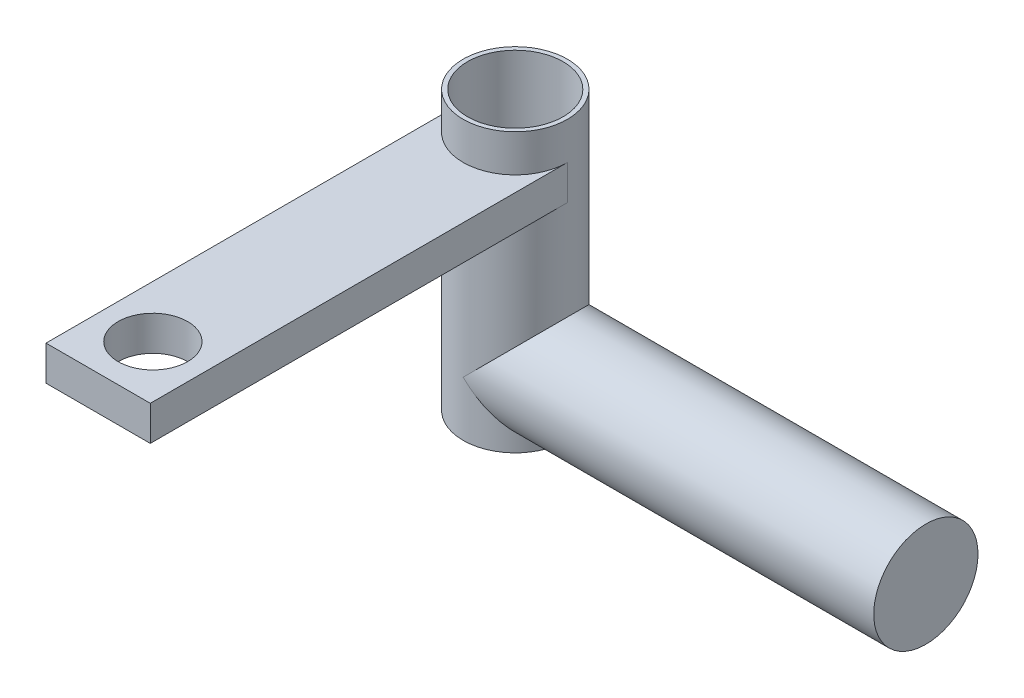
SolidWorks part; units mm, degrees
ref_plane "Front Plane" through (0, 0, 0) normal (0, 0, 1) x (1, 0, 0)
ref_plane "Top Plane" through (0, 0, 0) normal (0, 1, 0) x (1, 0, 0)
ref_plane "Right Plane" through (0, 0, 0) normal (1, 0, 0) x (0, 0, -1)
sketch "Sketch1" plane through (0, 0, 0) normal (0, 1, 0) x (1, 0, 0)
  circle A0 centre (0, 0) radius 9.525
  dimension "D1" = 19.05
extrude "Sleeve" add sketch "Sketch1" along normal blind 50.8
sketch "Sketch2" plane through (0, 0, 0) normal (0, 0, 1) x (1, 0, 0)
  line L0 (0, -10.4775) -> (0, 10.4775) construction
  line L1 (9.525, 43.975) -> (-9.525, 43.975)
  line L2 (9.525, 43.975) -> (9.525, 37.625)
  line L3 (9.525, 37.625) -> (-9.525, 37.625)
  line L4 (-9.525, 43.975) -> (-9.525, 37.625)
  line L5 (9.525, 43.975) -> (-9.525, 37.625) construction
  line L6 (9.525, 37.625) -> (-9.525, 43.975) construction
  point P0 (0, 40.8)
  dimension "D1" = 6.35
  dimension "D2" = 19.05
  dimension "D3" = 40.8
extrude "Bracket" add sketch "Sketch2" along normal blind 76.2
sketch "Sketch4" plane through (0, 0, 0) normal (0, 1, 0) x (1, 0, 0)
  line L0 (0, -27.94) -> (0, 27.94) construction
  circle A0 centre (0, -66.2) radius 6.35
  dimension "D1" = 12.7
  dimension "D2" = 66.2
extrude "Bracket Hole" cut sketch "Sketch4" along normal through all
sketch "Sketch5" plane through (0, 0, 0) normal (1, 0, 0) x (0, 0, -1)
  line L0 (0, 27.94) -> (0, -27.94) construction
  circle A0 centre (0, 10) radius 9.525
  dimension "D2" = 19.05
  dimension "D1" = 10
extrude "Shaft" add sketch "Sketch5" along normal blind 75
sketch "Sketch6" plane through (0, 0, 0) normal (0, 1, 0) x (1, 0, 0)
  circle A0 centre (0, 0) radius 8.7313
  dimension "D1" = 17.4625
extrude "Sleeve Hole" cut sketch "Sketch6" along normal through all
equation "\"shaftDiameter\"= 25.4 / 4 * 3mm"
equation "\"shaftLength\"= 75mm"
equation "\"sleeveDiameter\"= 25.4 / 4 * 3mm"
equation "\"sleeveLength\"= 2 * 25.4mm"
equation "\"bracketLength\"= 3 * 25.4mm"
equation "\"D1@Sketch1\"=\"sleeveDiameter\""
equation "\"D1@Sleeve\" = \"sleeveLength\""
equation "\"D3@Sketch2\"=\"sleeveLength\"-10"
equation "\"D1@Bracket\" = \"bracketLength\""
equation "\"tieBarHoleDiameter\"= 25.4 / 2mm"
equation "\"D1@Sketch4\"=\"tieBarHoleDiameter\""
equation "\"D2@Sketch4\"=\"bracketLength\"-10"
equation "\"D2@Sketch5\"=\"shaftDiameter\""
equation "\"D1@Shaft\" = \"shaftLength\""
equation "\"sleeveWallThickness\"= 25.4 / 16"
equation "\"D1@Sketch6\"=\"sleeveDiameter\"-\"sleeveWallThickness\""
